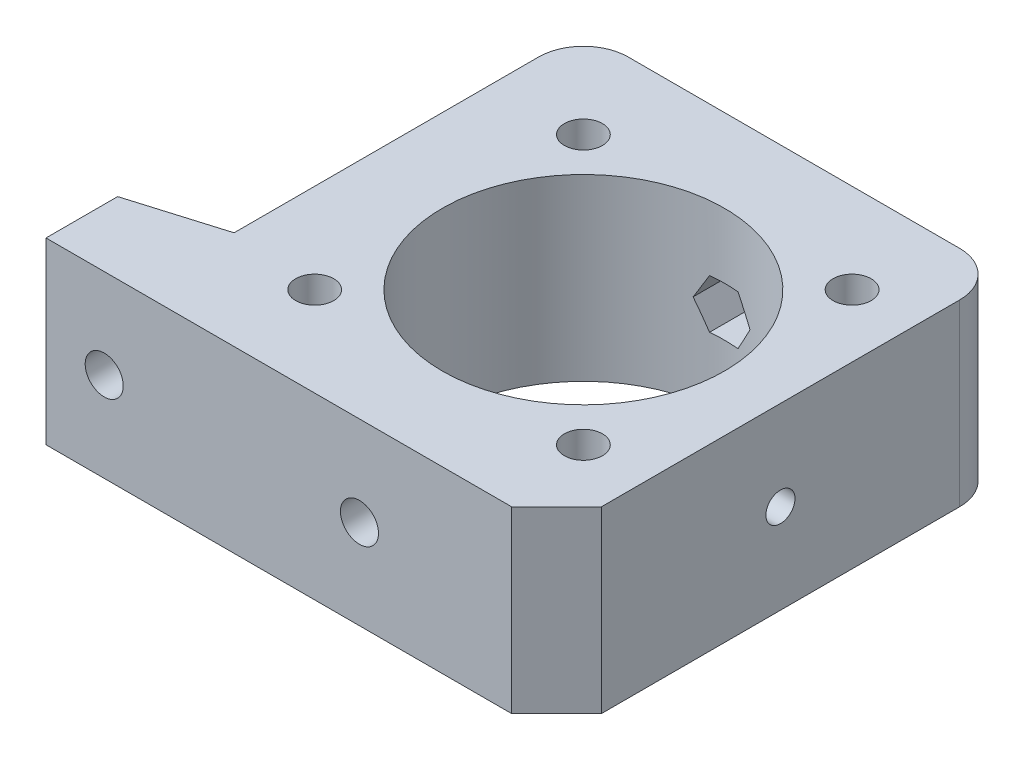
SolidWorks part; units mm, degrees
ref_plane "Alzado" through (0, 0, 0) normal (0, 0, 1) x (1, 0, 0)
ref_plane "Planta" through (0, 0, 0) normal (0, 1, 0) x (1, 0, 0)
ref_plane "Vista lateral" through (0, 0, 0) normal (1, 0, 0) x (0, 0, -1)
sketch "Croquis1" plane through (0, 0, 0) normal (0, 1, 0) x (1, 0, 0)
  line L0 (0, 25) -> (0, -25) construction
  line L1 (-25, 25) -> (25, 25)
  line L2 (-25, 25) -> (-25, -25)
  line L3 (-25, -25) -> (25, -25)
  line L4 (25, 25) -> (25, -25)
  line L5 (-25, 25) -> (25, -25) construction
  line L6 (-25, -25) -> (25, 25) construction
  line L7 (-25, -14) -> (-35, -17)
  line L8 (-35, -17) -> (-35, -25)
  line L9 (-35, -25) -> (-25, -25)
  circle A0 centre (-15, 15) radius 2.125
  circle A1 centre (15, 15) radius 2.125
  circle A2 centre (15, -15) radius 2.125
  circle A3 centre (-15, -15) radius 2.125
  circle A4 centre (0, 0) radius 15.75
  point P0 (0, 0)
  point P25 (0, -25)
  dimension "D3" = 4.25
  dimension "D7" = 31.5
  dimension "D1" = 50
  dimension "D2" = 50
  dimension "D4" = 10
  dimension "D5" = 2
  dimension "D8" = 8
  dimension "D9" = 10
  dimension "D12" = 3
  dimension "D6" = 2
extrude "Saliente-Extruir1" add sketch "Croquis1" against normal blind 20
sketch "Croquis3" plane through (0, 0, 25) normal (0, 0, 1) x (1, 0, 0)
  line L3 (-25, -20) -> (-25, 0) construction
  circle A0 centre (-28.5, -10) radius 2.125
  circle A1 centre (0, -10) radius 2.125
  dimension "D1" = 4.25
  dimension "D2" = 3.5
extrude "Cortar-Extruir1" cut sketch "Croquis3" against normal up to next
sketch "Croquis4" plane through (0, 0, 25) normal (0, 0, 1) x (1, 0, 0)
  line L1 (-28.5, -14.0415) -> (-25, -12.0207)
  line L2 (-25, -12.0207) -> (-25, -7.9793)
  line L3 (-25, -7.9793) -> (-28.5, -5.9585)
  line L4 (-28.5, -5.9585) -> (-32, -7.9793)
  line L5 (-32, -7.9793) -> (-32, -12.0207)
  line L6 (-32, -12.0207) -> (-28.5, -14.0415)
  line L7 (2.0207, -13.5) -> (4.0415, -10)
  line L8 (4.0415, -10) -> (2.0207, -6.5)
  line L9 (2.0207, -6.5) -> (-2.0207, -6.5)
  line L10 (-2.0207, -6.5) -> (-4.0415, -10)
  line L11 (-4.0415, -10) -> (-2.0207, -13.5)
  line L12 (-2.0207, -13.5) -> (2.0207, -13.5)
  circle A0 centre (-28.5, -10) radius 3.5 construction
  circle A1 centre (0, -10) radius 3.5 construction
  dimension "D1" = 7
  dimension "D2" = 7
extrude "Cortar-Extruir2" cut sketch "Croquis4" against normal up to next from offset 5 offset against normal yes
sketch "Croquis5" plane through (0, -20, 0) normal (0, -1, 0) x (1, 0, 0)
  line L1 (-11.0405, 13.9391) -> (-12.1014, 17.8986)
  line L2 (-12.1014, 17.8986) -> (-16.0609, 18.9595)
  line L3 (-16.0609, 18.9595) -> (-18.9595, 16.0609)
  line L4 (-18.9595, 16.0609) -> (-17.8986, 12.1014)
  line L5 (-17.8986, 12.1014) -> (-13.9391, 11.0405)
  line L6 (-13.9391, 11.0405) -> (-11.0405, 13.9391)
  line L7 (11.0405, 13.9391) -> (13.9391, 11.0405)
  line L8 (13.9391, 11.0405) -> (17.8986, 12.1014)
  line L9 (17.8986, 12.1014) -> (18.9595, 16.0609)
  line L10 (18.9595, 16.0609) -> (16.0609, 18.9595)
  line L11 (16.0609, 18.9595) -> (12.1014, 17.8986)
  line L12 (12.1014, 17.8986) -> (11.0405, 13.9391)
  line L13 (-13.9391, -11.0405) -> (-17.8986, -12.1014)
  line L14 (-17.8986, -12.1014) -> (-18.9595, -16.0609)
  line L15 (-18.9595, -16.0609) -> (-16.0609, -18.9595)
  line L16 (-16.0609, -18.9595) -> (-12.1014, -17.8986)
  line L17 (-12.1014, -17.8986) -> (-11.0405, -13.9391)
  line L18 (-11.0405, -13.9391) -> (-13.9391, -11.0405)
  line L19 (18.9595, -16.0609) -> (17.8986, -12.1014)
  line L20 (17.8986, -12.1014) -> (13.9391, -11.0405)
  line L21 (13.9391, -11.0405) -> (11.0405, -13.9391)
  line L22 (11.0405, -13.9391) -> (12.1014, -17.8986)
  line L23 (12.1014, -17.8986) -> (16.0609, -18.9595)
  line L24 (16.0609, -18.9595) -> (18.9595, -16.0609)
  circle A0 centre (-15, 15) radius 3.55 construction
  circle A3 centre (15, 15) radius 3.55 construction
  circle A4 centre (-15, -15) radius 3.55 construction
  circle A5 centre (15, -15) radius 3.55 construction
  dimension "D1" = 7.1
  dimension "D2" = 7.1
  dimension "D3" = 7.1
  dimension "D4" = 7.1
extrude "Cortar-Extruir3" cut sketch "Croquis5" against normal blind 10
sketch "Sketch1" plane through (0, 0, 0) normal (0, 1, 0) x (1, 0, 0)
  line L0 (-35, -25) -> (25, -25) construction
  line L1 (22, -25) -> (25, -25)
  line L2 (22, -25) -> (22, 35)
  line L3 (22, 35) -> (25, 35)
  line L4 (25, -25) -> (25, 35)
  line L5 (15, -15) -> (15, 15) construction
  dimension "D1" = 60
  dimension "D2" = 22
extrude "Cut-Extrude1" cut sketch "Sketch1" against normal through all
fillet "Redondeo1" radius 5 2 edges at (-25, -10, -25) (22, -10, -25)
sketch "Sketch2" plane through (0, 0, 0) normal (0, 1, 0) x (1, 0, 0)
  line L0 (22, -25) -> (22, 20) construction
  line L1 (-22, 20) -> (22, 20)
  line L2 (-22, 20) -> (-22, -20)
  line L3 (-22, -20) -> (22, -20)
  line L4 (22, 20) -> (22, -20)
  line L5 (-22, 20) -> (22, -20) construction
  line L6 (-22, -20) -> (22, 20) construction
  line L7 (22, -20) -> (17, -25)
  line L8 (-35, -25) -> (22, -25) construction
  line L9 (17, -25) -> (22, -25)
  line L10 (22, -25) -> (22, -20)
  point P0 (0, 0)
  line M11 (-35, -25) -> (22, -25)
  line M12 (22, -25) -> (22, 20)
  dimension "D1" = 40
  dimension "D2" = 45
extrude "Cut-Extrude2" cut sketch "Sketch2" against normal through all contours L7 M12 M11
sketch "Sketch3" plane through (22, 0, 0) normal (1, 0, 0) x (0, 0, -1)
  circle A0 centre (0, -10) radius 1.625
  dimension "D1" = 3.25
extrude "Cut-Extrude3" cut sketch "Sketch3" against normal blind 10
sketch "Sketch4" plane through (22, 0, 0) normal (1, 0, 0) x (0, 0, -1)
  line L1 (1.5877, -12.75) -> (3.1754, -10)
  line L2 (3.1754, -10) -> (1.5877, -7.25)
  line L3 (1.5877, -7.25) -> (-1.5877, -7.25)
  line L4 (-1.5877, -7.25) -> (-3.1754, -10)
  line L5 (-3.1754, -10) -> (-1.5877, -12.75)
  line L6 (-1.5877, -12.75) -> (1.5877, -12.75)
  circle A0 centre (0, -10) radius 2.75 construction
  dimension "D1" = 5.5
extrude "Cut-Extrude4" cut sketch "Sketch4" against normal up to next from offset 4 offset against normal yes
sketch "Sketch5" plane through (0, 0, -25) normal (0, 0, -1) x (-1, 0, 0)
  circle A0 centre (0, -10) radius 1.625
  dimension "D1" = 3.25
extrude "Cut-Extrude5" cut sketch "Sketch5" against normal up to next
sketch "Sketch6" plane through (0, 0, -25) normal (0, 0, -1) x (-1, 0, 0)
  line L1 (1.5877, -12.75) -> (3.1754, -10)
  line L2 (3.1754, -10) -> (1.5877, -7.25)
  line L3 (1.5877, -7.25) -> (-1.5877, -7.25)
  line L4 (-1.5877, -7.25) -> (-3.1754, -10)
  line L5 (-3.1754, -10) -> (-1.5877, -12.75)
  line L6 (-1.5877, -12.75) -> (1.5877, -12.75)
  circle A0 centre (0, -10) radius 2.75 construction
  dimension "D1" = 5.5
extrude "Cut-Extrude6" cut sketch "Sketch6" against normal up to next from offset 4 offset against normal yes
mirror "Simetría1" about plane through (0, -20, 0) normal (0, 1, 0) of "Saliente-Extruir1", "Cortar-Extruir1", "Cortar-Extruir2", "Cortar-Extruir3", "Cut-Extrude1", "Redondeo1", "Cut-Extrude2", "Cut-Extrude3", "Cut-Extrude4", "Cut-Extrude5", "Cut-Extrude6"
sketch "Croquis6" plane through (0, 0, -25) normal (0, 0, -1) x (-1, 0, 0)
  line L1 (-22, -20) -> (35, -20)
  line L2 (-22, -20) -> (-22, 0)
  line L3 (-22, 0) -> (35, 0)
  line L4 (35, -20) -> (35, 0)
extrude "Cortar-Extruir4" cut sketch "Croquis6" against normal through all
mirror "Simetría4" about plane through (22, -20, 25) normal (0, -1, 0) of bodies 113
sketch "Croquis7" plane through (0, 0, -25) normal (0, 0, -1) x (-1, 0, 0)
  line L0 (-22, -40) -> (-22, 0) construction
  line L1 (-22, -20) -> (35, -20)
  line L2 (-22, -20) -> (-22, -40)
  line L3 (-22, -40) -> (35, -40)
  line L4 (35, -20) -> (35, -40)
extrude "Cortar-Extruir5" cut sketch "Croquis7" against normal through all
